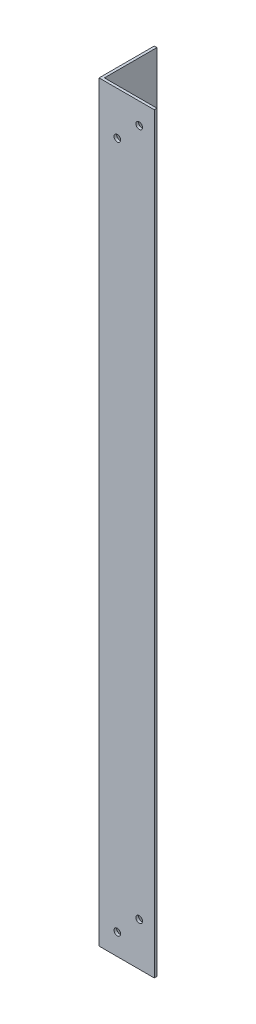
SolidWorks part; units mm, degrees
ref_plane "Front" through (0, 0, 0) normal (0, 0, 1) x (1, 0, 0)
ref_plane "Top" through (0, 0, 0) normal (0, 1, 0) x (1, 0, 0)
ref_plane "Right" through (0, 0, 0) normal (1, 0, 0) x (0, 0, -1)
sketch "Эскиз1" plane through (0, 0, 0) normal (0, 1, 0) x (1, 0, 0)
  line L0 (0, 0) -> (0, 25)
  line L1 (0, 0) -> (25, 0)
  line L2 (25, 0) -> (25, 1.2)
  line L3 (0, 25) -> (1.2, 25)
  line L4 (1.2, 25) -> (1.2, 1.2)
  line L5 (1.2, 1.2) -> (25, 1.2)
extrude "Бобышка-Вытянуть1" add sketch "Эскиз1" along normal blind 340.5
sketch "Эскиз2" plane through (0, 0, -1.2) normal (0, 0, -1) x (-1, 0, 0)
  line L0 (-1.2, 340.5) -> (-1.2, 330.863) construction
  line L1 (-1.2, 340.5) -> (-1.2, 0) construction
  line L2 (-1.2, 330.863) -> (-18.17, 330.863) construction
  line L3 (-18.17, 330.863) -> (-8.2705, 320.9635) construction
  line L4 (-1.2, 0) -> (-1.2, 9.673) construction
  line L5 (-1.2, 340.5) -> (-1.2, 0) construction
  line L6 (-1.2, 9.673) -> (-8.2705, 9.673) construction
  line L7 (-18.17, 19.5725) -> (-8.2705, 9.673) construction
  circle A0 centre (-18.17, 330.863) radius 1.5
  circle A1 centre (-8.2705, 320.9635) radius 1.5
  circle A2 centre (-18.17, 19.5725) radius 1.5
  circle A3 centre (-8.2705, 9.673) radius 1.5
extrude "Вырез-Вытянуть1" cut sketch "Эскиз2" against normal through all
